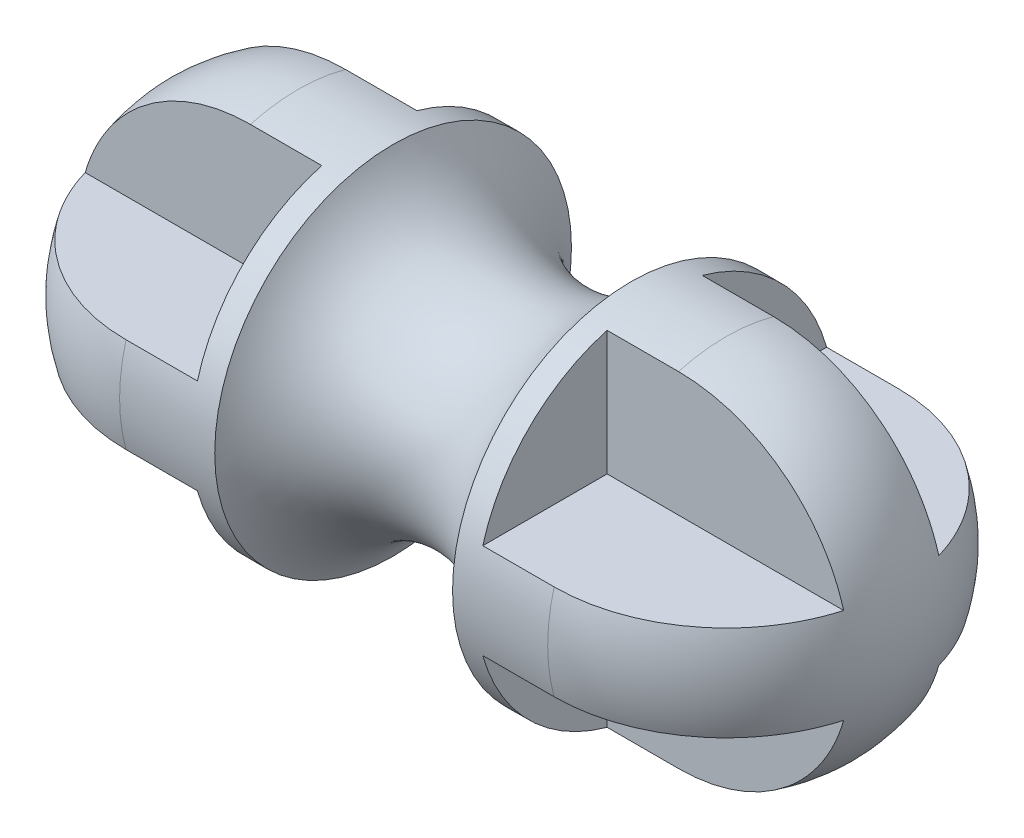
SolidWorks part; units mm, degrees
ref_plane "前视基准面" through (0, 0, 0) normal (0, 0, 1) x (1, 0, 0)
ref_plane "上视基准面" through (0, 0, 0) normal (0, 1, 0) x (1, 0, 0)
ref_plane "右视基准面" through (0, 0, 0) normal (1, 0, 0) x (0, 0, -1)
other "Configuration Table"
sketch "草图1" plane through (0, 0, 0) normal (0, 0, 1) x (1, 0, 0)
  line L0 (-232.2366, 0) -> (232.2366, 0) construction
  line L1 (0, 176.6575) -> (0, -176.6575) construction
  line L2 (45, 37.5) -> (25, 37.5)
  line L3 (-45, 37.5) -> (-25, 37.5)
  line L4 (-82.5, 0) -> (82.5, 0)
  arc A0 (82.5, 0) -> (45, 37.5) centre (45, 0) ccw
  arc A1 (25, 37.5) -> (-25, 37.5) centre (0, 50.8333) cw
  arc A2 (-82.5, 0) -> (-45, 37.5) centre (-45, 0) cw
  point P14 (0, 22.5)
  dimension "D1" = 37.5
  dimension "D2" = 165
  dimension "D3" = 50
  dimension "D4" = 15
revolve "旋转1" add sketch "草图1" angle 360 about L4
ref_plane "基准面1" through (30, 0, 0) normal (1, 0, 0) x (0, 0, -1)
sketch "草图2" plane through (30, 0, 0) normal (1, 0, 0) x (0, 0, -1)
  line L0 (0, 0) -> (0, -37.5) construction
  line L1 (-37.5, 0) -> (37.5, 0) construction
  line L2 (10, 36.1421) -> (10, 10)
  line L3 (10, 10) -> (36.1421, 10)
  line L4 (-10, 10) -> (-36.1421, 10)
  line L5 (-10, 36.1421) -> (-10, 10)
  line L6 (-10, -10) -> (-36.1421, -10)
  line L7 (-10, -36.1421) -> (-10, -10)
  line L8 (10, -10) -> (36.1421, -10)
  line L9 (10, -36.1421) -> (10, -10)
  circle A0 centre (0, 0) radius 37.5 construction
  arc A1 (-36.1421, -10) -> (-10, -36.1421) centre (0, 0) ccw
  arc A2 (36.1421, 10) -> (10, 36.1421) centre (0, 0) ccw
  arc A3 (-10, 36.1421) -> (-36.1421, 10) centre (0, 0) ccw
  arc A4 (10, -36.1421) -> (36.1421, -10) centre (0, 0) ccw
  point P8 (0, 0)
  point P9 (0, 0)
  dimension "D1" = 20
  dimension "D2" = 20
extrude "切除-拉伸1" cut sketch "草图2" along normal through all
mirror "镜向1" about plane through (0, 0, 0) normal (1, 0, 0) of "切除-拉伸1"
